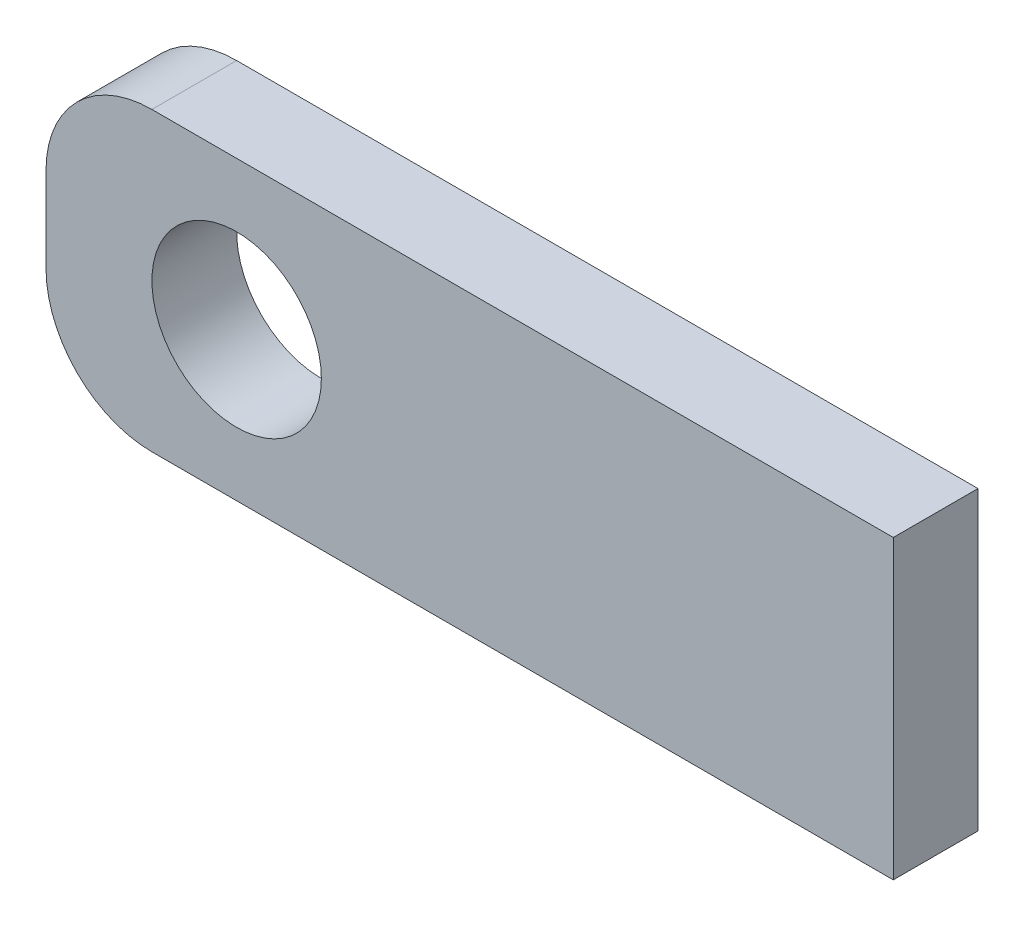
SolidWorks part; units mm, degrees
ref_plane "Front" through (0, 0, 0) normal (0, 0, 1) x (1, 0, 0)
ref_plane "Top" through (0, 0, 0) normal (0, 1, 0) x (1, 0, 0)
ref_plane "Right" through (0, 0, 0) normal (1, 0, 0) x (0, 0, -1)
sketch "Sketch1" plane through (0, 0, 0) normal (0, 0, 1) x (1, 0, 0)
  line L1 (0, 0) -> (-40, 0)
  line L2 (0, 0) -> (0, 14)
  line L3 (0, 14) -> (-40, 14)
  line L4 (-40, 0) -> (-40, 14)
  circle A0 centre (-31, 7) radius 4
  dimension "D3" = 8
  dimension "D4" = 9
  dimension "D1" = 40
  dimension "D2" = 14
extrude "Boss-Extrude1" add sketch "Sketch1" along normal blind 4
fillet "Fillet1" radius 5 2 edges at (-40, 0, 2) (-40, 14, 2)
